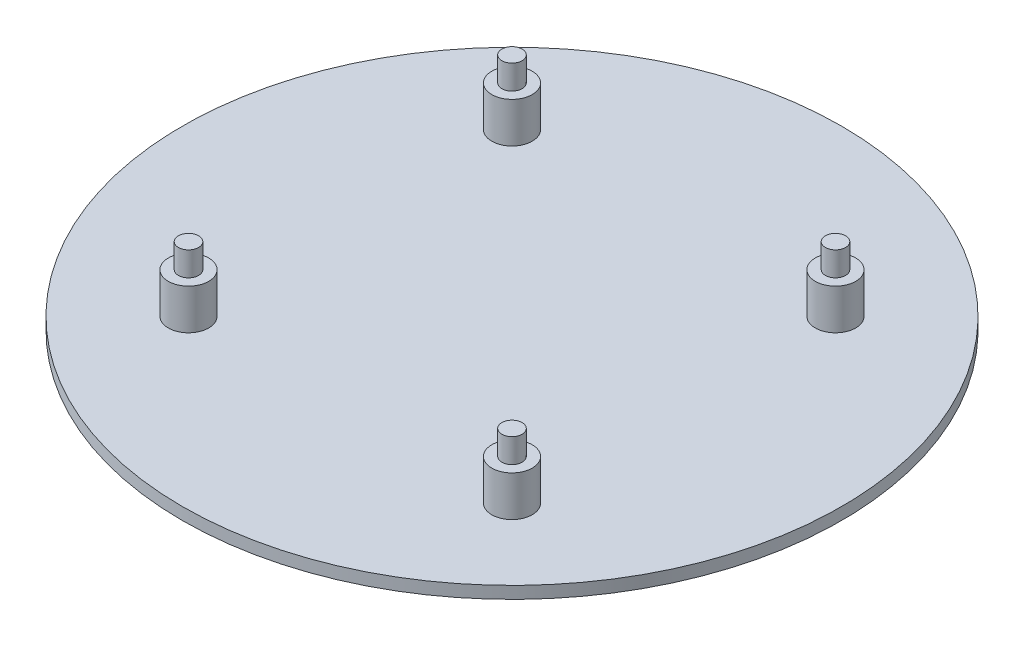
SolidWorks part; units mm, degrees
ref_plane "Front Plane" through (0, 0, 0) normal (0, 0, 1) x (1, 0, 0)
ref_plane "Top Plane" through (0, 0, 0) normal (0, 1, 0) x (1, 0, 0)
ref_plane "Right Plane" through (0, 0, 0) normal (1, 0, 0) x (0, 0, -1)
sketch "Sketch3" plane through (0, 0, 0) normal (0, 1, 0) x (1, 0, 0)
  circle A0 centre (0, 0) radius 81.5
  dimension "D1" = 163
extrude "Boss-Extrude1" add sketch "Sketch3" along normal blind 3
sketch "Sketch4" plane through (0, 3, 0) normal (0, 1, 0) x (1, 0, 0)
  line L0 (0, -1.65) -> (0, 1.65) construction
  line L1 (-1.65, 0) -> (1.65, 0) construction
  line L2 (0, 113.5976) -> (0, -118.0689) construction
  line L3 (119.3264, 0) -> (-114.8552, 0) construction
  circle A0 centre (-40, 40) radius 5
  circle A1 centre (40, 40) radius 5
  circle A2 centre (40, -40) radius 5
  circle A3 centre (-40, -40) radius 5
  dimension "D3" = 10
  dimension "D1" = 40
  dimension "D2" = 40
extrude "Boss-Extrude2" add sketch "Sketch4" along normal blind 10
sketch "Sketch5" plane through (0, 13, 0) normal (0, 1, 0) x (1, 0, 0)
  circle A0 centre (-40, 40) radius 2.5
  circle A1 centre (40, 40) radius 2.5
  circle A2 centre (40, -40) radius 2.5
  circle A3 centre (-40, -40) radius 2.5
  dimension "D1" = 5
extrude "Boss-Extrude3" add sketch "Sketch5" along normal blind 6
